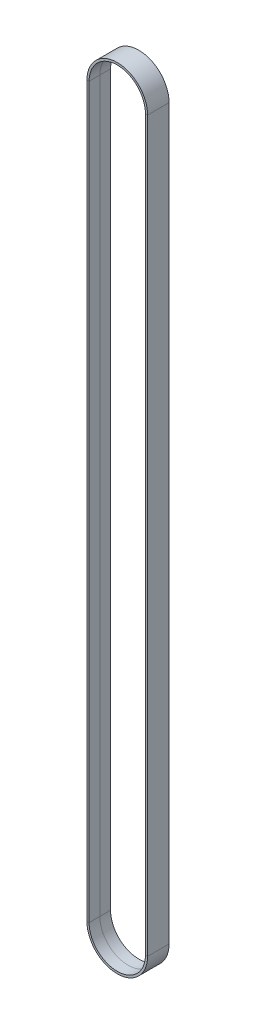
SolidWorks part; units mm, degrees
ref_plane "Спереди" through (0, 0, 0) normal (0, 0, 1) x (1, 0, 0)
ref_plane "Сверху" through (0, 0, 0) normal (0, 1, 0) x (1, 0, 0)
ref_plane "Справа" through (0, 0, 0) normal (1, 0, 0) x (0, 0, -1)
sketch "Эскиз2" plane through (0, 0, 0) normal (0, 0, 1) x (1, 0, 0)
  line L0 (0, 0) -> (1, 0) construction
  line L1 (0, 0) -> (0, 1) construction
  line L2 (26.25, 0) -> (26.25, -678.6787)
  line L3 (-26.25, -678.6787) -> (-26.25, 0)
  arc A0 (-26.25, 0) -> (26.25, 0) centre (0, 0) cw
  arc A1 (26.25, -678.6787) -> (-26.25, -678.6787) centre (0, -678.6787) cw
ref_plane "Плоскость1" through (0, 0, 0) normal (0, 0, 1) x (1, 0, 0)
sketch "Эскиз3" plane through (0, 0, 0) normal (0, 0, 1) x (1, 0, 0)
  line L0 (-26.25, -678.6787) -> (-26.25, 0) construction
  line L1 (26.25, 0) -> (26.25, -678.6787) construction
  line L2 (-26.25, -678.6787) -> (-26.25, 0)
  line L3 (26.25, 0) -> (26.25, -678.6787)
  arc A0 (-26.25, -678.6787) -> (26.25, -678.6787) centre (0, -678.6787) ccw construction
  arc A1 (26.25, 0) -> (-26.25, 0) centre (0, 0) ccw construction
  arc A2 (-26.25, -678.6787) -> (26.25, -678.6787) centre (0, -678.6787) ccw
  arc A3 (26.25, 0) -> (-26.25, 0) centre (0, 0) ccw
ref_plane "Плоскость2" through (0, 0, 0) normal (0, 1, 0) x (1, 0, 0)
sketch "Эскиз4" plane through (0, 0, 0) normal (0, 1, 0) x (1, 0, 0)
  line L0 (15.1713, -10) -> (14.1, -10) construction
  line L2 (-26.25, 0) -> (-26.25, -10)
  line L3 (-26.25, -10) -> (-28.25, -10)
  line L5 (14.1, 10) -> (15.1713, 10) construction
  line L11 (-26.25, 0) -> (-26.25, 10)
  line L12 (-26.25, 10) -> (-28.25, 10)
  line L14 (-28.25, 10) -> (-28.25, -10)
  dimension "D1" = 2
  dimension "D2" = 2
sweep "По траектории1" add profiles "Эскиз4" path "Эскиз3"
